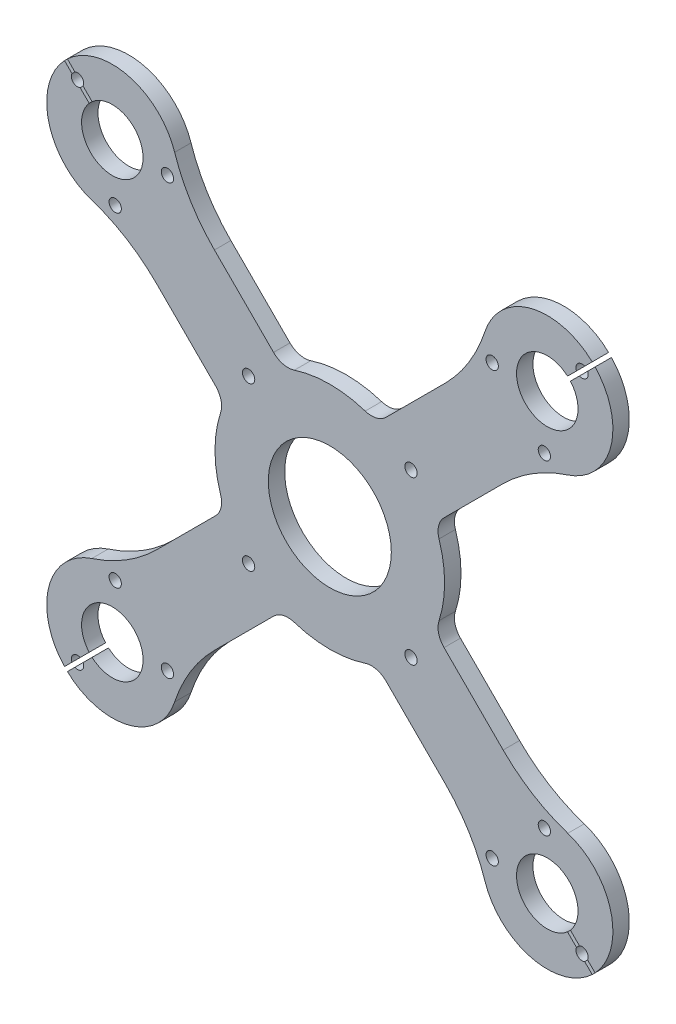
SolidWorks part; units mm, degrees
material "Acrylic (Medium-high impact)"
ref_plane "Front Plane" through (0, 0, 0) normal (0, 0, 1) x (1, 0, 0)
ref_plane "Top Plane" through (0, 0, 0) normal (0, 1, 0) x (1, 0, 0)
ref_plane "Right Plane" through (0, 0, 0) normal (1, 0, 0) x (0, 0, -1)
sketch "Sketch1" plane through (0, 0, 0) normal (0, 0, 1) x (1, 0, 0)
  line L0 (37.1302, 51.2723) -> (11.4222, 25.5643)
  line L1 (25.5643, 11.4222) -> (51.2723, 37.1302)
  line L2 (53.033, 53.033) -> (61.5183, 61.5183) construction
  line L3 (51.2723, -37.1302) -> (25.5643, -11.4222)
  line L4 (11.4222, -25.5643) -> (37.1302, -51.2723)
  line L5 (-37.1302, -51.2723) -> (-11.4222, -25.5643)
  line L6 (-25.5643, -11.4222) -> (-51.2723, -37.1302)
  line L7 (-51.2723, 37.1302) -> (-25.5643, 11.4222)
  line L8 (0, 28) -> (0, -28) construction
  line L9 (-28, 0) -> (28, 0) construction
  line L10 (0, 0) -> (53.033, 53.033) construction
  line L11 (-11.4222, 25.5643) -> (-37.1302, 51.2723)
  line L13 (53.033, 53.033) -> (52.3259, 39.598) construction
  line L14 (39.598, 52.3259) -> (53.033, 53.033) construction
  line L15 (47.7297, 58.3363) -> (58.3363, 47.7297) construction
  circle A0 centre (52.3259, 39.598) radius 1.5
  circle A1 centre (39.598, 52.3259) radius 4 construction
  circle A2 centre (19.799, -19.799) radius 1.5
  circle A3 centre (61.5183, 61.5183) radius 1.5
  circle A4 centre (-19.799, -19.799) radius 1.5
  circle A5 centre (19.799, 19.799) radius 1.5
  circle A6 centre (-19.799, 19.799) radius 1.5
  circle A7 centre (52.3259, 39.598) radius 4 construction
  circle A8 centre (39.598, 52.3259) radius 1.5
  arc A9 (37.1302, 51.2723) -> (51.2723, 37.1302) centre (53.033, 53.033) ccw construction
  arc A10 (51.2723, 37.1302) -> (37.1302, 51.2723) centre (53.033, 53.033) ccw
  circle A11 centre (53.033, 53.033) radius 7.5
  arc A12 (11.4222, 25.5643) -> (-11.4222, 25.5643) centre (0, 0) ccw
  arc A13 (37.1302, -51.2723) -> (51.2723, -37.1302) centre (53.033, -53.033) ccw
  circle A14 centre (53.033, -53.033) radius 7.5
  circle A15 centre (61.5183, -61.5183) radius 1.5
  circle A16 centre (52.3259, -39.598) radius 1.5
  circle A17 centre (39.598, -52.3259) radius 1.5
  arc A18 (-51.2723, -37.1302) -> (-37.1302, -51.2723) centre (-53.033, -53.033) ccw
  circle A19 centre (-53.033, -53.033) radius 7.5
  circle A20 centre (0, 0) radius 28 construction
  circle A21 centre (-61.5183, -61.5183) radius 1.5
  circle A22 centre (-39.598, -52.3259) radius 1.5
  circle A23 centre (-52.3259, -39.598) radius 1.5
  arc A24 (-37.1302, 51.2723) -> (-51.2723, 37.1302) centre (-53.033, 53.033) ccw
  circle A25 centre (-53.033, 53.033) radius 7.5
  circle A26 centre (-61.5183, 61.5183) radius 1.5
  circle A27 centre (-52.3259, 39.598) radius 1.5
  circle A28 centre (-39.598, 52.3259) radius 1.5
  arc A30 (-25.5643, 11.4222) -> (-25.5643, -11.4222) centre (0, 0) ccw
  arc A32 (-11.4222, -25.5643) -> (11.4222, -25.5643) centre (0, 0) ccw
  arc A34 (25.5643, -11.4222) -> (25.5643, 11.4222) centre (0, 0) ccw
  circle A58 centre (0, 0) radius 15
  point P61 (0, 0)
  point P69 (0, 0)
  point P74 (0, 0)
  dimension "D2" = 10
  dimension "D3" = 3
  dimension "D4" = 56
  dimension "D7" = 3
  dimension "D10" = 75
  dimension "D11" = 12
  dimension "D8" = 15
  dimension "D16" = 4
  dimension "D17" = 8
  dimension "D6" = 30
  dimension "D9" = 3
  dimension "D13" = 16
  dimension "D14" = 18
  dimension "D15" = 20
  dimension "D5" = 45
  dimension "D12" = 0
extrude "Boss-Extrude1" add sketch "Sketch1" along normal blind 4
sketch "Sketch3" plane through (0, 0, 4) normal (0, 0, 1) x (1, 0, 0)
  line L0 (61.5183, 61.5183) -> (53.033, 53.033) construction
  line L1 (63.9932, 64.7003) -> (57.971, 58.6781)
  line L2 (57.971, 58.6781) -> (58.6781, 57.971)
  line L3 (58.6781, 57.971) -> (64.7003, 63.9932)
  line L4 (64.7003, 63.9932) -> (63.9932, 64.7003)
  line L5 (58.6781, -57.971) -> (57.971, -58.6781)
  line L6 (57.971, -58.6781) -> (63.9932, -64.7003)
  line L7 (64.7003, -63.9932) -> (58.6781, -57.971)
  line L8 (63.9932, -64.7003) -> (64.7003, -63.9932)
  line L9 (-57.971, -58.6781) -> (-58.6781, -57.971)
  line L10 (-58.6781, -57.971) -> (-64.7003, -63.9932)
  line L11 (-63.9932, -64.7003) -> (-57.971, -58.6781)
  line L12 (-64.7003, -63.9932) -> (-63.9932, -64.7003)
  line L13 (-58.6781, 57.971) -> (-57.971, 58.6781)
  line L14 (-57.971, 58.6781) -> (-63.9932, 64.7003)
  line L15 (-64.7003, 63.9932) -> (-58.6781, 57.971)
  line L16 (-63.9932, 64.7003) -> (-64.7003, 63.9932)
  arc A0 (51.2723, 37.1302) -> (37.1302, 51.2723) centre (53.033, 53.033) ccw construction
  circle A1 centre (53.033, 53.033) radius 7.5 construction
  point P28 (0, 0)
  dimension "D1" = 1
  dimension "D2" = 4
extrude "Cut-Extrude2" cut sketch "Sketch3" against normal through all
fillet "Fillet3" radius 40 8 edges at (37.1302, 51.2723, 2) (51.2723, 37.1302, 2) (51.2723, -37.1302, 2) (37.1302, -51.2723, 2) (-37.1302, -51.2723, 2) (-51.2723, -37.1302, 2) (-51.2723, 37.1302, 2) (-37.1302, 51.2723, 2)
fillet "Fillet4" radius 5 8 edges at (11.4222, 25.5643, 2) (-11.4222, 25.5643, 2) (-25.5643, 11.4222, 2) (-25.5643, -11.4222, 2) (-11.4222, -25.5643, 2) (11.4222, -25.5643, 2) (25.5643, -11.4222, 2) (25.5643, 11.4222, 2)
